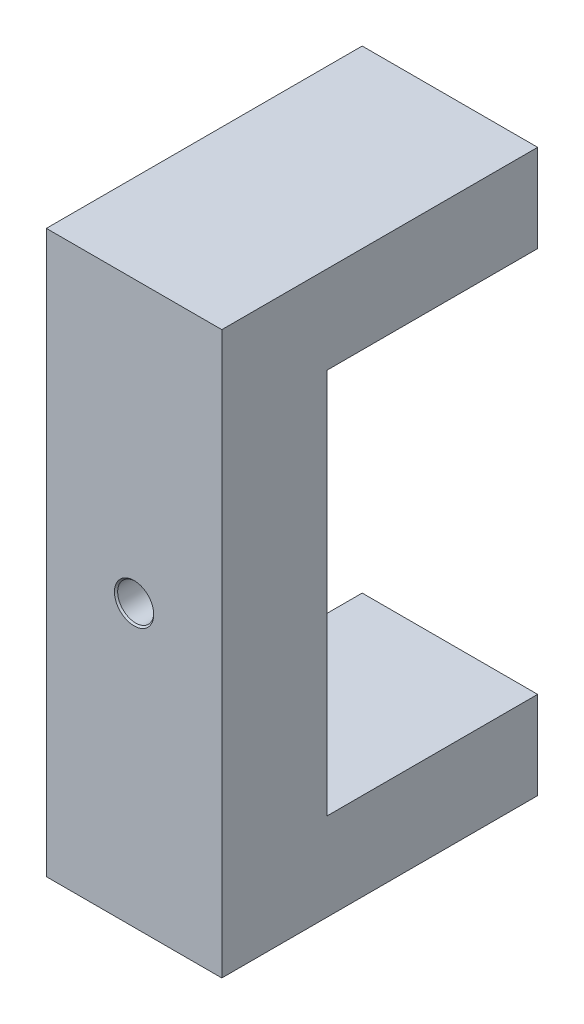
SolidWorks part; units mm, degrees
ref_plane "Front Plane" through (0, 0, 0) normal (0, 0, 1) x (1, 0, 0)
ref_plane "Top Plane" through (0, 0, 0) normal (0, 1, 0) x (1, 0, 0)
ref_plane "Right Plane" through (0, 0, 0) normal (1, 0, 0) x (0, 0, -1)
sketch "Sketch1" plane through (0, 0, 0) normal (1, 0, 0) x (0, 0, -1)
  line L0 (0, 34.925) -> (0, 50.8)
  line L1 (0, 50.8) -> (-57.15, 50.8)
  line L2 (-57.15, 50.8) -> (-57.15, -50.8)
  line L3 (-57.15, -50.8) -> (0, -50.8)
  line L4 (0, -50.8) -> (0, -34.925)
  line L5 (0, -34.925) -> (-38.1, -34.925)
  line L6 (-38.1, -34.925) -> (-38.1, 34.925)
  line L7 (-38.1, 34.925) -> (0, 34.925)
  point P3 (-38.1, 0)
  dimension "D1" = 15.875
  dimension "D2" = 38.1
  dimension "D3" = 19.05
  dimension "D4" = 69.85
extrude "Boss-Extrude1" add sketch "Sketch1" along normal mid plane 31.75
hole_wizard "F (0.257) Diameter Hole1" positions "Sketch3" profile "Sketch2" hole size "F" standard "ANSI Inch" end condition through all
sketch "Sketch3" plane through (0, 0, 57.15) normal (0, 0, 1) x (1, 0, 0)
  point P0 (0, 0)
sketch "Sketch2" plane through (0, 0, 57.15) normal (1, 0, 0) x (0, -1, 0)
  line L0 (0, 0) -> (0, 19.05)
  line L1 (0, 19.05) -> (3.556, 19.05)
  line L2 (3.2639, 18.7579) -> (3.2639, 0.2921)
  line L3 (3.2639, 0.2921) -> (3.556, 0)
  line L5 (3.556, 0) -> (0, 0)
  line L6 (-3.2639, 0.2921) -> (-3.556, 0) construction
  line L7 (3.556, 19.05) -> (3.2639, 18.7579)
  line L8 (-3.556, 19.05) -> (-3.2639, 18.7579) construction
  line L11 (0, -6.35) -> (0, 107.95) construction
  dimension "Thru Hole Dia." = 6.5278
  dimension "Thru Hole Depth" = 19.05
  dimension "Near C'Sink Dia." = 7.112
  dimension "Near C'Sink Angle" = 90
  dimension "Far C'Sink Dia." = 7.112
  dimension "Far C'Sink Angle" = 90
